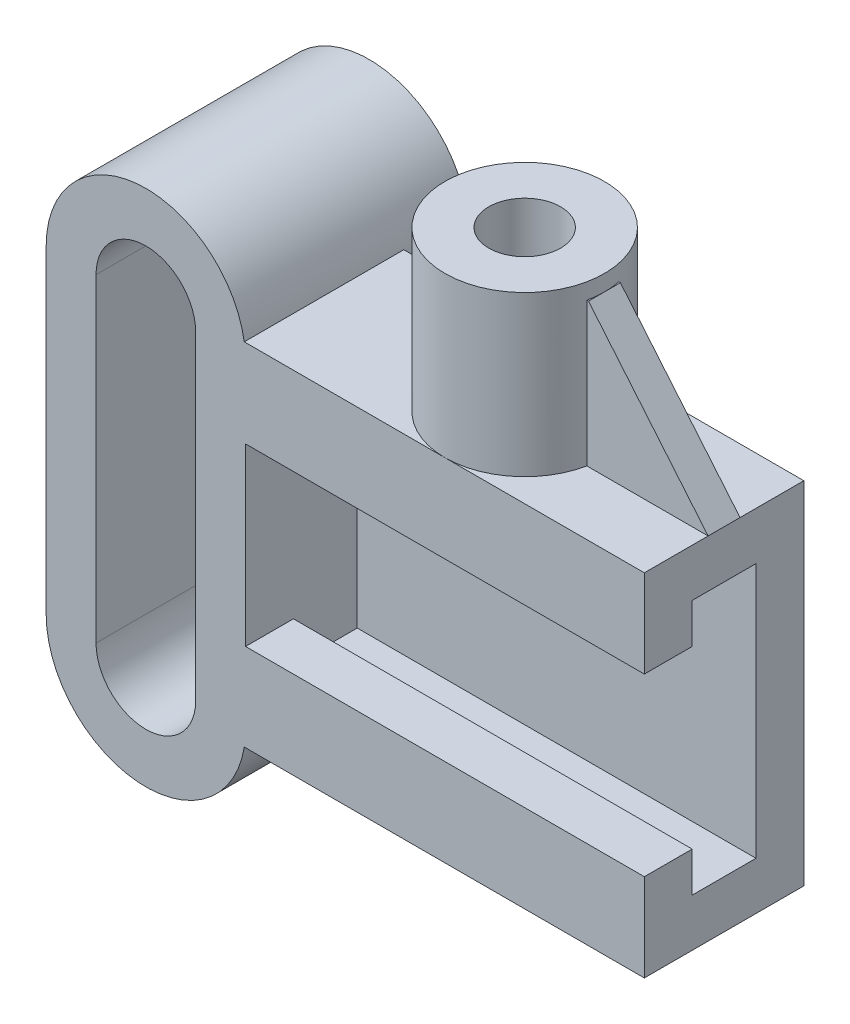
SolidWorks part; units mm, degrees
ref_plane "Front Plane" through (0, 0, 0) normal (0, 0, 1) x (1, 0, 0)
ref_plane "Top Plane" through (0, 0, 0) normal (0, 1, 0) x (1, 0, 0)
ref_plane "Right Plane" through (0, 0, 0) normal (1, 0, 0) x (0, 0, -1)
sketch "Sketch1" plane through (0, 0, 0) normal (1, 0, 0) x (0, 0, -1)
  line L0 (-14, 16) -> (-14, 11)
  line L1 (-14, 11) -> (-20, 11)
  line L2 (-20, 11) -> (-20, 22)
  line L3 (-20, 22) -> (0, 22)
  line L4 (0, 22) -> (0, -22)
  line L5 (0, -22) -> (-20, -22)
  line L6 (-20, -22) -> (-20, -11)
  line L7 (-20, -11) -> (-14, -11)
  line L8 (-14, -11) -> (-14, -16)
  line L9 (-14, -16) -> (-6, -16)
  line L10 (-6, -16) -> (-6, 16)
  line L11 (-6, 16) -> (-14, 16)
  line L12 (0, 0) -> (-36.0618, 0) construction
  dimension "D1" = 32
  dimension "D2" = 44
  dimension "D3" = 8
  dimension "D4" = 22
  dimension "D5" = 6
  dimension "D6" = 20
extrude "Boss-Extrude1" add sketch "Sketch1" along normal blind 62.5
sketch "Sketch3" plane through (0, 0, 20) normal (0, 0, 1) x (1, 0, 0)
  line L0 (0, 20) -> (0, -20) construction
  line L1 (0, 16) -> (0, -16) construction
  line L2 (0, -11) -> (0, -22) construction
  line L3 (12.5, 20) -> (12.5, -20)
  line L4 (-12.5, 20) -> (-12.5, -20)
  arc A1 (12.5, 20) -> (-12.5, 20) centre (0, 20) ccw
  arc A2 (-12.5, -20) -> (12.5, -20) centre (0, -20) ccw
  point P8 (0, 0)
  point P13 (0, 6.2891)
  dimension "D1" = 12.5
  dimension "D2" = 40
extrude "Boss-Extrude2" add sketch "Sketch3" against normal blind 28
sketch "Sketch4" plane through (0, 0, 20) normal (0, 0, 1) x (1, 0, 0)
  line L0 (0, 20) -> (0, -20) construction
  line L1 (6.25, 20) -> (6.25, -20)
  line L2 (-6.25, 20) -> (-6.25, -20)
  arc A0 (6.25, 20) -> (-6.25, 20) centre (0, 20) ccw
  arc A1 (-6.25, -20) -> (6.25, -20) centre (0, -20) ccw
  point P3 (0, 0)
  point P8 (0, 0)
  dimension "D1" = 6.25
  dimension "D2" = 40
extrude "Cut-Extrude1" cut sketch "Sketch4" against normal through all
sketch "Sketch5" plane through (0, 22, 0) normal (0, 1, 0) x (1, 0, 0)
  line L0 (62.5, 0) -> (12.339, 0) construction
  line L1 (62.5, -20) -> (12.339, -20) construction
  circle A0 centre (37.5, -10) radius 10
  dimension "D1" = 37.5
extrude "Boss-Extrude3" add sketch "Sketch5" along normal blind 20
hole_wizard "Hole1" positions "Sketch6" profile "Sketch7" legacy
sketch "Sketch6" plane through (0, 42, 0) normal (0, 1, 0) x (1, 0, 0)
  point P0 (37.5, -10)
sketch "Sketch7" plane through (37.5, 42, 10) normal (1, 0, 0) x (0, 0, 1)
  line L0 (0, 0) -> (0, 16)
  line L1 (0, 16) -> (4.5, 16)
  line L2 (4.5, 16) -> (4.5, 0)
  line L3 (4.5, 0) -> (0, 0)
  line L4 (0, 110) -> (0, -10) construction
  dimension "Diameter" = 9
  dimension "Depth" = 16
sketch "Sketch9" plane through (0, 0, 20) normal (0, 0, 1) x (1, 0, 0)
  line L0 (47.5, 40) -> (62.5, 22)
  line L1 (47.5, 22) -> (47.5, 42) construction
  line L2 (62.5, 22) -> (47.5, 22)
  line L3 (62.5, 22) -> (37.5, 22) construction
  line L5 (47.5, 40) -> (46.5, 40)
  line L6 (46.5, 40) -> (46.5, 22)
  line L7 (46.5, 22) -> (47.5, 22)
  dimension "D1" = 18
  dimension "D2" = 1
extrude "Boss-Extrude5" add sketch "Sketch9" along normal mid plane 4 from offset 10
